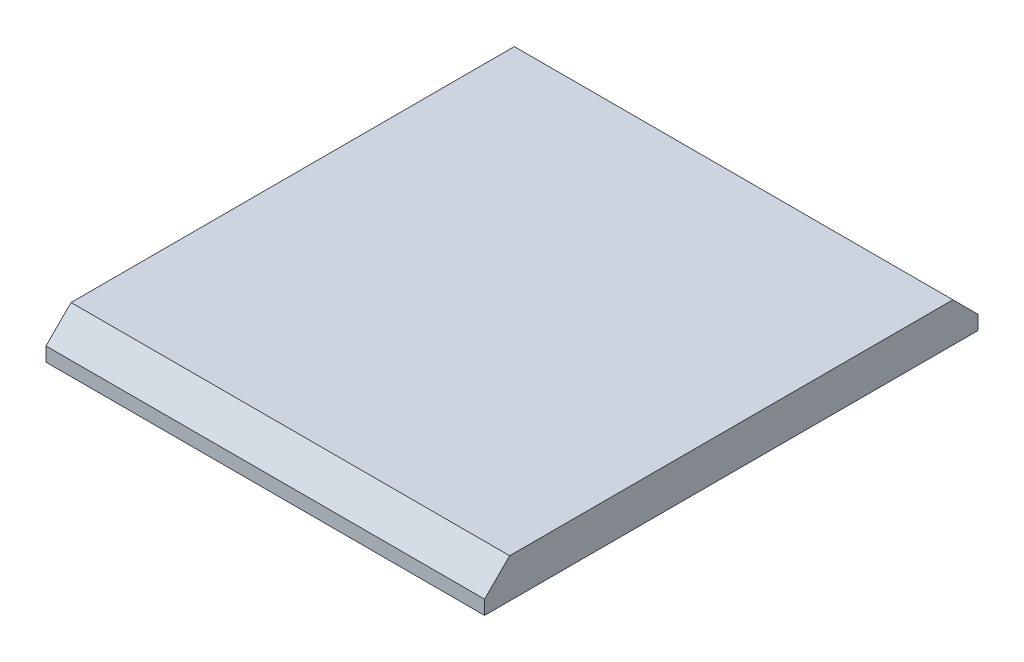
SolidWorks part; units mm, degrees
material "Polyurethane Foam Flexible"
ref_plane "Front Plane" through (0, 0, 0) normal (0, 0, 1) x (1, 0, 0)
ref_plane "Top Plane" through (0, 0, 0) normal (0, 1, 0) x (1, 0, 0)
ref_plane "Right Plane" through (0, 0, 0) normal (1, 0, 0) x (0, 0, -1)
sketch "Sketch1" plane through (0, 0, 0) normal (0, 1, 0) x (1, 0, 0)
  line L1 (0, 0) -> (355.6, 0)
  line L2 (0, 0) -> (0, 400.05)
  line L3 (0, 400.05) -> (355.6, 400.05)
  line L4 (355.6, 0) -> (355.6, 400.05)
  dimension "D1" = 355.6
  dimension "D2" = 400.05
extrude "Boss-Extrude1" add sketch "Sketch1" along normal blind 31.75
sketch "Sketch2" plane through (355.6, 0, 0) normal (1, 0, 0) x (0, 0, -1)
  line L0 (0, 31.75) -> (0, 11.43)
  line L1 (0, 31.75) -> (0, 0) construction
  line L2 (0, 31.75) -> (20.32, 31.75)
  line L3 (0, 31.75) -> (400.05, 31.75) construction
  line L4 (20.32, 31.75) -> (0, 11.43)
  line L5 (400.05, 31.75) -> (400.05, 11.43)
  line L6 (400.05, 31.75) -> (400.05, 0) construction
  line L7 (400.05, 31.75) -> (379.73, 31.75)
  line L8 (379.73, 31.75) -> (400.05, 11.43)
extrude "Cut-Extrude1" cut sketch "Sketch2" against normal blind 369.57
